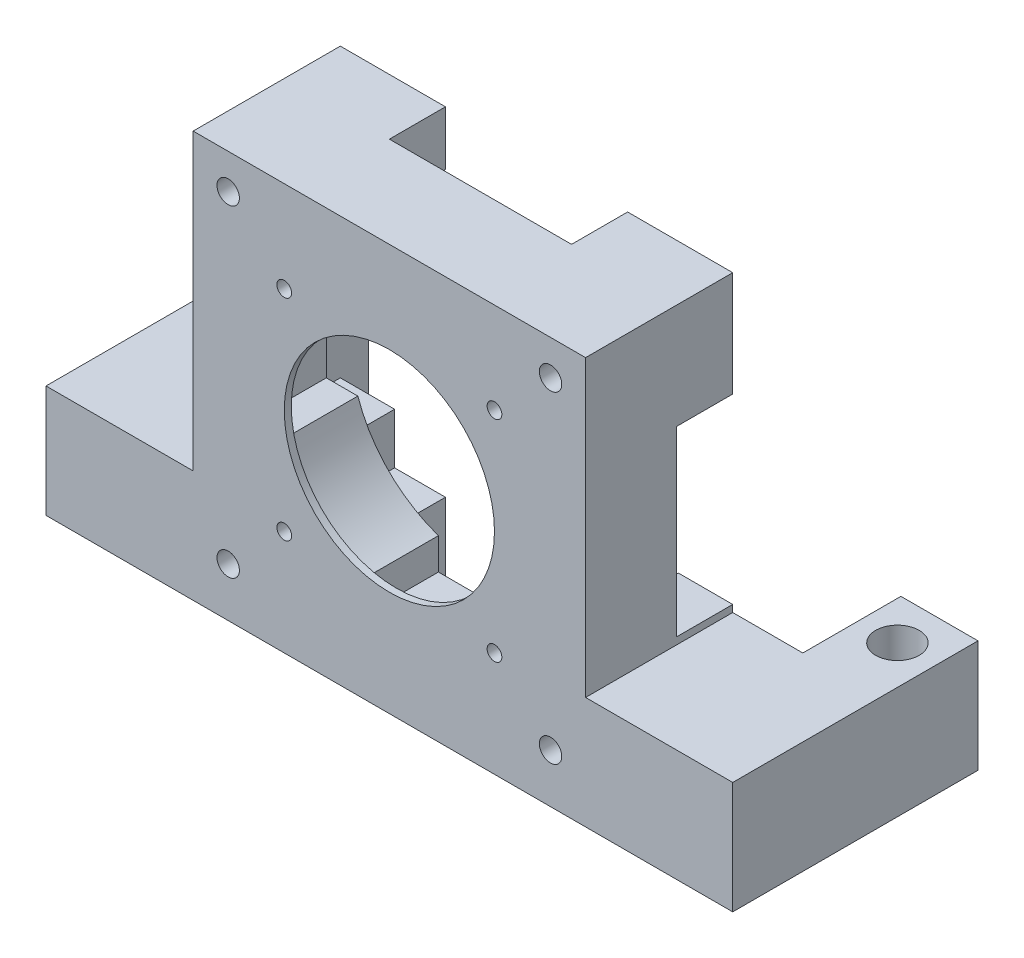
SolidWorks part; units mm, degrees
ref_plane "Front Plane" through (0, 0, 0) normal (0, 0, 1) x (1, 0, 0)
ref_plane "Top Plane" through (0, 0, 0) normal (0, 1, 0) x (1, 0, 0)
ref_plane "Right Plane" through (0, 0, 0) normal (1, 0, 0) x (0, 0, -1)
sketch "Sketch1" plane through (0, 0, 0) normal (0, 0, 1) x (1, 0, 0)
  circle A0 centre (0, 0) radius 18.5
  dimension "D1" = 37
sketch "Sketch2" plane through (0, 0, 0) normal (0, 0, 1) x (1, 0, 0)
  line L1 (-28, 28) -> (28, 28)
  line L2 (-28, 28) -> (-28, -28)
  line L3 (-28, -28) -> (28, -28)
  line L4 (28, 28) -> (28, -28)
  line L5 (-28, 28) -> (28, -28) construction
  line L6 (-28, -28) -> (28, 28) construction
  point P0 (0, 0)
  dimension "D1" = 56
  dimension "D2" = 56
sketch "Sketch3" plane through (0, 0, 0) normal (0, 0, 1) x (1, 0, 0)
  line L0 (-28, -28) -> (28, 28) construction
  circle A0 centre (15, 15) radius 1.05
  dimension "D2" = 2.1
  dimension "D1" = 15
extrude "Boss-Extrude1" add sketch "Sketch2" along normal blind 13 and the other way blind 8
extrude "Cut-Extrude1" cut sketch "Sketch1" along normal blind 12 and the other way through all
sketch "Sketch4" plane through (0, 0, 0) normal (0, 0, 1) x (1, 0, 0)
  circle A0 centre (0, 0) radius 15
  dimension "D1" = 30
extrude "Cut-Extrude2" cut sketch "Sketch4" along normal through all
sketch "Sketch5" plane through (0, 0, 0) normal (0, 0, 1) x (1, 0, 0)
  line L1 (6, 22) -> (-6, 22)
  line L2 (6, 22) -> (6, 14)
  line L3 (6, 14) -> (-6, 14)
  line L4 (-6, 22) -> (-6, 14)
  line L5 (6, 22) -> (-6, 14) construction
  line L6 (6, 14) -> (-6, 22) construction
  point P0 (0, 18)
  dimension "D1" = 12
  dimension "D2" = 0
  dimension "D3" = 18
  dimension "D4" = 8
extrude "Cut-Extrude3" cut sketch "Sketch5" against normal through all and the other way blind 12
sketch "Sketch6" plane through (0, 0, 0) normal (0, 0, 1) x (1, 0, 0)
  line L1 (20.25, 20.25) -> (-20.25, 20.25)
  line L2 (20.25, 20.25) -> (20.25, -20.25)
  line L3 (20.25, -20.25) -> (-20.25, -20.25)
  line L4 (-20.25, 20.25) -> (-20.25, -20.25)
  line L5 (20.25, 20.25) -> (-20.25, -20.25) construction
  line L6 (20.25, -20.25) -> (-20.25, 20.25) construction
  point P0 (0, 0)
  dimension "D1" = 40.5
  dimension "D2" = 40.5
extrude "Cut-Extrude4" cut sketch "Sketch6" against normal through all
extrude "Cut-Extrude5" cut sketch "Sketch3" against normal through all and the other way through all
pattern_circular "CirPattern1" count 4 over 360 about axis through (0, 0, 0) along (0, 0, 1) of "Cut-Extrude5"
sketch "Sketch7" plane through (0, -28, 0) normal (0, -1, 0) x (1, 0, 0)
  line L0 (-28, 13) -> (28, 13) construction
  line L1 (-49, 13) -> (49, 13)
  line L2 (-49, 13) -> (-49, -8)
  line L3 (-49, -8) -> (49, -8)
  line L4 (49, 13) -> (49, -8)
  line L6 (-28, -8) -> (28, -8) construction
  dimension "D1" = 49
  dimension "D2" = 98
extrude "Boss-Extrude2" add sketch "Sketch7" along normal blind 2
sketch "Sketch8" plane through (0, -30, 0) normal (0, -1, 0) x (1, 0, 0)
  line L0 (49, 13) -> (-49, 13) construction
  line L1 (49, 13) -> (39, 13)
  line L2 (49, 13) -> (49, -22)
  line L3 (49, -22) -> (38, -22)
  line L4 (38, -8) -> (38, -22)
  line L5 (28, 13) -> (39, 13)
  line L6 (28, 13) -> (28, -8)
  line L7 (28, -8) -> (38, -8)
  line L9 (-49, -8) -> (49, -8) construction
  line L10 (28, -8) -> (28, 13) construction
  dimension "D1" = 10
  dimension "D2" = 35
  dimension "D3" = 10
extrude "Boss-Extrude3" add sketch "Sketch8" against normal blind 16
mirror "Mirror1" about plane through (0, 0, 0) normal (1, 0, 0) of "Boss-Extrude3"
sketch "Sketch9" plane through (0, -14, 0) normal (0, 1, 0) x (1, 0, 0)
  line L1 (-38, 22) -> (-49, 22) construction
  line L2 (0, -11.55) -> (0, 11.55) construction
  circle A0 centre (-43.5, 16) radius 3.1
  dimension "D2" = 6.2
  dimension "D1" = 43.5
  dimension "D3" = 6
extrude "Cut-Extrude6" cut sketch "Sketch9" against normal through all
mirror "Mirror2" about plane through (0, 0, 0) normal (1, 0, 0) of "Cut-Extrude6"
sketch "Sketch10" plane through (0, 0, 0) normal (0, 0, -1) x (-1, 0, 0)
  line L0 (20.25, -20.25) -> (-20.25, -20.25) construction
  line L1 (-13, -20.25) -> (13, -20.25)
  line L2 (-13, -20.25) -> (-13, -30)
  line L3 (-13, -30) -> (13, -30)
  line L4 (13, -20.25) -> (13, -30)
  line L5 (-13, -20.25) -> (13, -30) construction
  line L6 (-13, -30) -> (13, -20.25) construction
  line L7 (38, -30) -> (-38, -30) construction
  point P0 (0, -25.125)
  dimension "D1" = 26
  dimension "D2" = 0
extrude "Cut-Extrude7" cut sketch "Sketch10" along normal through all
sketch "Sketch11" plane through (0, 0, -8) normal (0, 0, -1) x (-1, 0, 0)
  circle A0 centre (-23, 23) radius 1.6
  circle A1 centre (0, 0) radius 32.5269 construction
  dimension "D1" = 3.2
  dimension "D2" = 23
  dimension "D3" = 23
extrude "Cut-Extrude8" cut sketch "Sketch11" against normal through all
mirror "Mirror3" about plane through (0, 0, 0) normal (0, 1, 0) of "Cut-Extrude8"
mirror "Mirror4" about plane through (0, 0, 0) normal (1, 0, 0) of "Mirror3", "Cut-Extrude8"
pattern_circular "CirPattern2" count 4 over 360 about axis through (0, 0, 0) along (0, 0, 1) of "Cut-Extrude3"
pattern_circular "CirPattern3" count 4 over 360 about axis through (0, 0, 0) along (0, 0, 1) of "Cut-Extrude7"
